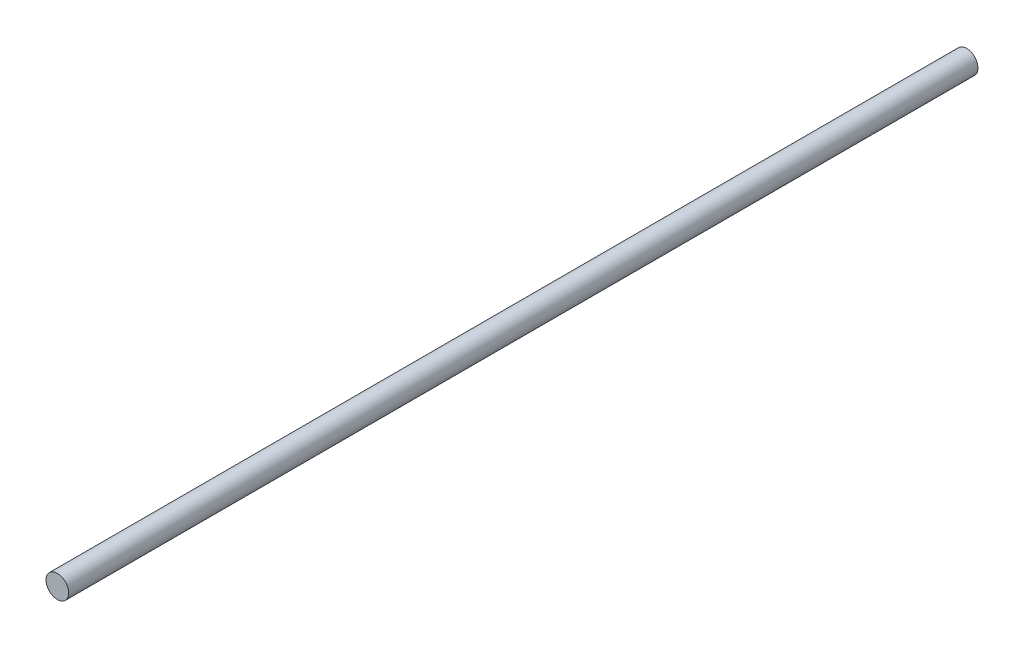
SolidWorks part; units mm, degrees
ref_plane "Plan de face" through (0, 0, 0) normal (0, 0, 1) x (1, 0, 0)
ref_plane "Plan de dessus" through (0, 0, 0) normal (0, 1, 0) x (1, 0, 0)
ref_plane "Plan de droite" through (0, 0, 0) normal (1, 0, 0) x (0, 0, -1)
sketch "Esquisse1" plane through (0, 0, 0) normal (0, 0, 1) x (1, 0, 0)
  circle A0 centre (0, 0) radius 2.5
  dimension "D1" = 5
extrude "Boss.-Extru.1" add sketch "Esquisse1" along normal blind 200
